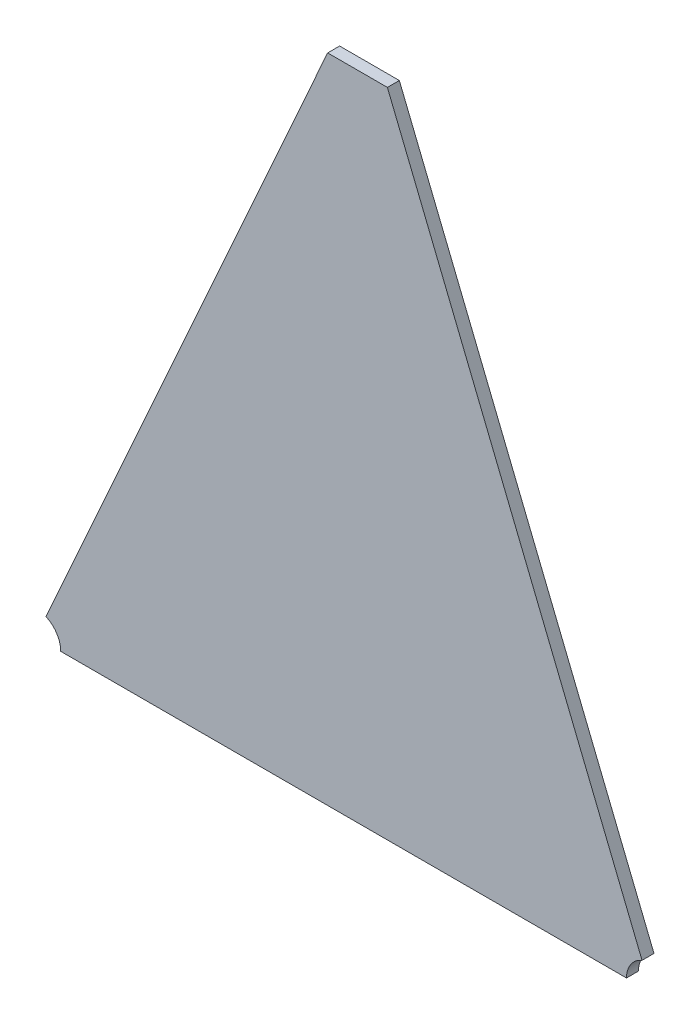
SolidWorks part; units mm, degrees
ref_plane "Front Plane" through (0, 0, 0) normal (0, 0, 1) x (1, 0, 0)
ref_plane "Top Plane" through (0, 0, 0) normal (0, 1, 0) x (1, 0, 0)
ref_plane "Right Plane" through (0, 0, 0) normal (1, 0, 0) x (0, 0, -1)
sketch "Sketch2" plane through (0, 0, 0) normal (0, 0, 1) x (1, 0, 0)
  line L0 (-189.7401, 245.3834) -> (-375.9085, -170.4146)
  line L1 (-375.9085, -170.4146) -> (16.7755, -170.4146)
  line L2 (16.7755, -170.4146) -> (-151.6401, 245.3834)
  line L4 (-189.7401, 245.3834) -> (-151.6401, 245.3834)
  dimension "D1" = 415.798
  dimension "D2" = 415.798
  dimension "D3" = 67.95
  dimension "D4" = 38.1
  dimension "D5" = 392.684
extrude "Boss-Extrude1" add sketch "Sketch2" along normal blind 7.62 contours L0 L1 L2 L4
sketch "Sketch5" plane through (0, 0, 0) normal (0, 0, -1) x (-1, 0, 0)
  circle A0 centre (375.9085, -170.4146) radius 15.875
  dimension "D1" = 31.75
extrude "Cut-Extrude2" cut sketch "Sketch5" against normal blind 50.8
sketch "Sketch6" plane through (0, 0, 0) normal (0, 0, -1) x (-1, 0, 0)
  circle A0 centre (-16.7755, -170.4146) radius 15.875
  dimension "D1" = 31.75
extrude "Cut-Extrude3" cut sketch "Sketch6" against normal blind 50.8 contours A0
ref_plane "Plane1" through (-360.0335, -170.4146, 0) normal (1, 0, 0) x (0, 0, -1)
sketch "Sketch8" plane through (0, 0, 0) normal (0, 0, -1) x (-1, 0, 0)
  line L0 (254.9716, -43.4146) -> (147.0216, -43.4146) construction
  line L1 (360.0335, -170.4146) -> (-0.9005, -170.4146) construction
  line L2 (254.9716, -170.4146) -> (254.9716, 97.7332) construction
  line L3 (254.9716, -43.4146) -> (254.9716, -170.4146) construction
  line L4 (147.0216, -43.4146) -> (147.0216, -170.4146) construction
  line L5 (147.0216, -170.4146) -> (183.5239, -170.4146) construction
  line L6 (183.5239, -170.4146) -> (183.5239, -105.3906) construction
  line L7 (170.6901, 245.3834) -> (179.5665, -170.4146) construction
  line L8 (189.7401, 245.3834) -> (151.6401, 245.3834) construction
  line L9 (183.5239, -105.3906) -> (218.4489, -105.3906) construction
  line L10 (218.4489, -105.3906) -> (218.4489, -170.4146) construction
  line L11 (218.4489, -170.4146) -> (218.4489, -105.3906)
  line L12 (218.4489, -105.3906) -> (183.5239, -105.3906)
  line L13 (183.5239, -105.3906) -> (183.5239, -170.4146)
  line L14 (153.8492, -170.4146) -> (153.8492, -48.647) construction
  dimension "D1" = 268.1478
  dimension "D2" = 107.95
  dimension "D3" = 127
  dimension "D4" = 36.5023
  dimension "D5" = 65.024
  dimension "D6" = 34.925
  dimension "D7" = 121.7676
